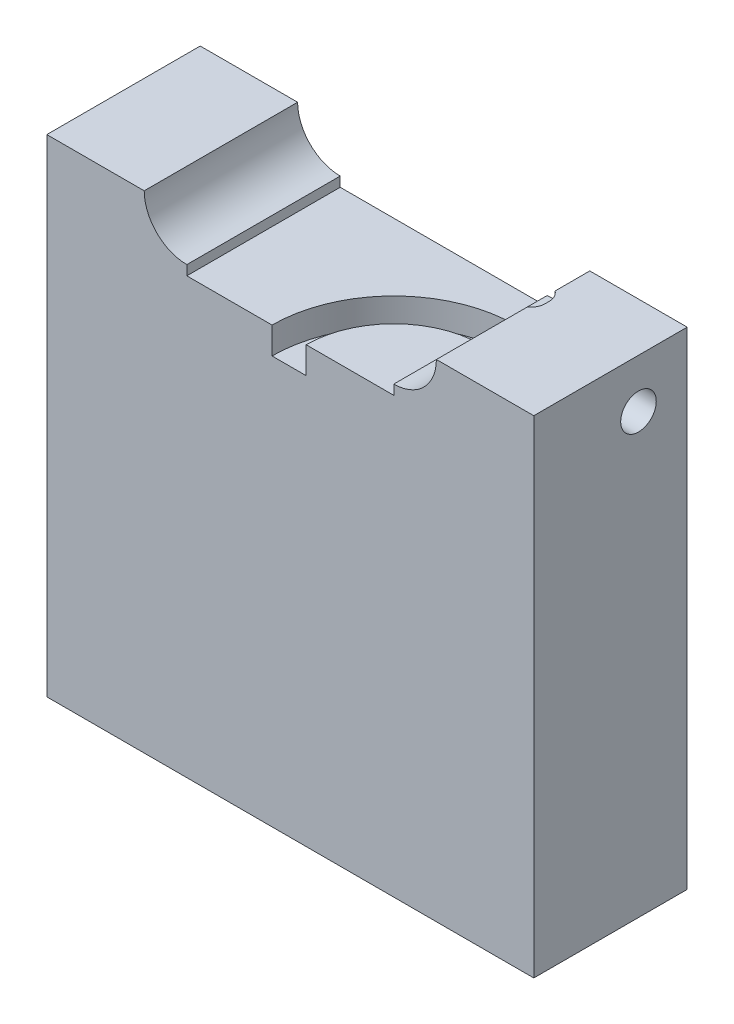
SolidWorks part; units mm, degrees
ref_plane "Front Plane" through (0, 0, 0) normal (0, 0, 1) x (1, 0, 0)
ref_plane "Top Plane" through (0, 0, 0) normal (0, 1, 0) x (1, 0, 0)
ref_plane "Right Plane" through (0, 0, 0) normal (1, 0, 0) x (0, 0, -1)
sketch "Sketch1" plane through (0, 0, 0) normal (0, 1, 0) x (1, 0, 0)
  line L1 (-12.7, -4.0005) -> (12.7, -4.0005)
  line L2 (-12.7, -4.0005) -> (-12.7, 4.0005)
  line L3 (-12.7, 4.0005) -> (12.7, 4.0005)
  line L4 (12.7, -4.0005) -> (12.7, 4.0005)
  line L5 (-12.7, -4.0005) -> (12.7, 4.0005) construction
  line L6 (-12.7, 4.0005) -> (12.7, -4.0005) construction
  point P0 (0, 0)
  dimension "D1" = 25.4
  dimension "D2" = 8.001
extrude "Boss-Extrude1" add sketch "Sketch1" along normal blind 25.4
sketch "Sketch2" plane through (0, 0, -4.0005) normal (0, 0, -1) x (-1, 0, 0)
  line L0 (5.3975, 25.4) -> (-5.3975, 25.4) construction
  line L1 (5.3975, 23.1775) -> (-5.3975, 23.1775)
  line L2 (5.3975, 27.6225) -> (-5.3975, 27.6225)
  line L3 (12.7, 25.4) -> (-12.7, 25.4) construction
  line L5 (-12.7, 25.4) -> (12.7, 25.4) construction
  line L6 (12.7, 25.4) -> (12.7, 0) construction
  line L7 (-12.7, 25.4) -> (-12.7, 0) construction
  arc A0 (5.3975, 23.1775) -> (5.3975, 27.6225) centre (5.3975, 25.4) ccw
  arc A1 (-5.3975, 27.6225) -> (-5.3975, 23.1775) centre (-5.3975, 25.4) ccw
  point P2 (0, 25.4)
  dimension "D2" = 10.795
  dimension "D3" = 4.445
extrude "Cut-Extrude1" cut sketch "Sketch2" against normal blind 25.4
ref_plane "Plane1" through (0, 23.1775, 0) normal (0, 1, 0) x (1, 0, 0)
sketch "Sketch4" plane through (0, 23.1775, 0) normal (0, 1, 0) x (1, 0, 0)
  line L0 (0, -9.1985) -> (0, 12.0201) construction
  line L1 (0.8255, -4.0005) -> (-0.9525, -4.0005)
  line L2 (5.3975, 0.5715) -> (7.1437, 0.5715)
  line L3 (7.9375, 1.3652) -> (7.9375, 1.5557)
  line L4 (7.1437, 2.3495) -> (5.3975, 2.3495)
  arc A0 (5.3975, 2.3495) -> (-0.9525, -4.0005) centre (5.3975, -4.0005) ccw
  arc A1 (5.3975, 0.5715) -> (0.8255, -4.0005) centre (5.3975, -4.0005) ccw
  arc A2 (7.9375, 1.3652) -> (7.1437, 0.5715) centre (7.1437, 1.3652) cw
  arc A3 (7.9375, 1.5557) -> (7.1437, 2.3495) centre (7.1437, 1.5557) ccw
  dimension "D1" = 12.7
  dimension "D2" = 9.144
  dimension "D3" = 2.54
  dimension "D4" = 0.7937
extrude "Cut-Extrude2" cut sketch "Sketch4" against normal blind 1.905 and the other way through all
ref_plane "Plane3" through (12.7, 0, 0) normal (1, 0, 0) x (0, 0, -1)
sketch "Sketch5" plane through (12.7, 0, 0) normal (1, 0, 0) x (0, 0, -1)
  line L0 (-4.0005, 25.4) -> (-4.0005, 0) construction
  line L1 (-4.0005, 25.4) -> (4.0005, 25.4) construction
  circle A0 centre (1.4605, 22.86) radius 0.9271
  dimension "D2" = 1.8542
  dimension "D1" = 5.461
  dimension "D3" = 2.54
extrude "Cut-Extrude3" cut sketch "Sketch5" against normal blind 6.35
sketch "Sketch6" plane through (0, 23.1775, 0) normal (0, 1, 0) x (1, 0, 0)
  line L1 (-5.3975, 4.0005) -> (5.3975, 4.0005)
  line L2 (-5.3975, 4.0005) -> (-5.3975, -4.0005)
  line L3 (-5.3975, -4.0005) -> (5.3975, -4.0005)
  line L4 (5.3975, 4.0005) -> (5.3975, -4.0005)
extrude "Cut-Extrude4" cut sketch "Sketch6" against normal blind 0.508
